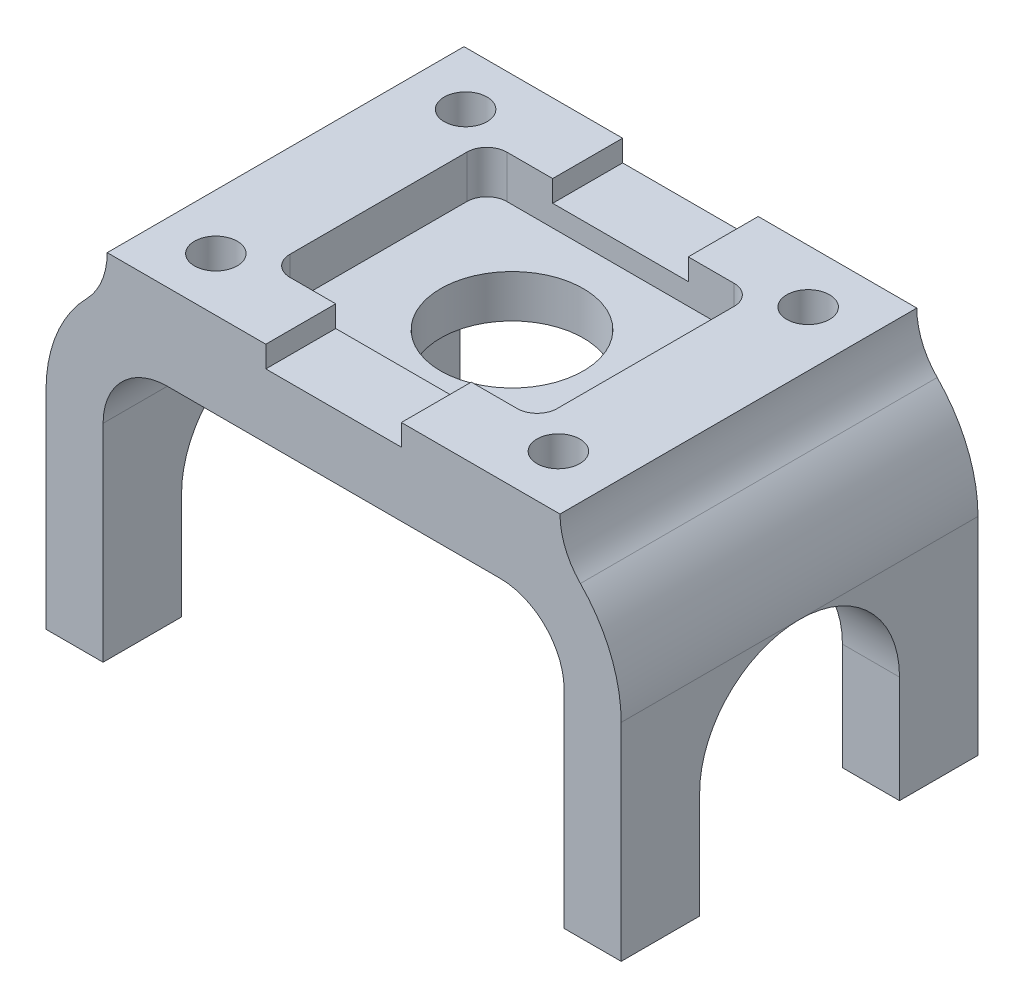
SolidWorks part; units mm, degrees
material "Plain Carbon Steel"
ref_plane "Front Plane" through (0, 0, 0) normal (0, 0, 1) x (1, 0, 0)
ref_plane "Top Plane" through (0, 0, 0) normal (0, 1, 0) x (1, 0, 0)
ref_plane "Right Plane" through (0, 0, 0) normal (1, 0, 0) x (0, 0, -1)
sketch "Sketch2" plane through (0, 0, 0) normal (0, 0, 1) x (1, 0, 0)
  line L0 (-29.591, 0) -> (29.591, 0)
  line L1 (41.021, -11.43) -> (41.021, -48.26)
  line L2 (41.021, -48.26) -> (51.181, -48.26)
  line L3 (51.181, -48.26) -> (51.181, -11.43)
  line L4 (40.2898, 15.24) -> (-40.2898, 15.24)
  line L5 (-51.181, -11.43) -> (-51.181, -48.26)
  line L6 (-51.181, -48.26) -> (-41.021, -48.26)
  line L7 (-41.021, -48.26) -> (-41.021, -11.43)
  line L8 (0, 0) -> (0, 94.6407) construction
  arc A0 (51.181, -11.43) -> (43.9202, 6.35) centre (25.781, -11.43) ccw
  arc A1 (43.9202, 6.35) -> (40.2898, 15.24) centre (52.9898, 15.24) cw
  arc A2 (-40.2898, 15.24) -> (-43.9202, 6.35) centre (-52.9898, 15.24) cw
  arc A3 (-43.9202, 6.35) -> (-51.181, -11.43) centre (-25.781, -11.43) ccw
  arc A4 (29.591, 0) -> (41.021, -11.43) centre (29.591, -11.43) cw
  arc A5 (-29.591, 0) -> (-41.021, -11.43) centre (-29.591, -11.43) ccw
  dimension "D1" = 36.83
  dimension "D4" = 12.7
  dimension "D5" = 25.4
  dimension "D2" = 10.16
  dimension "D3" = 15.24
  dimension "D6" = 82.042
  dimension "D7" = 63.5
extrude "Boss-Extrude1" add sketch "Sketch2" along normal mid plane 63.5
sketch "Sketch3" plane through (51.181, 0, 0) normal (1, 0, 0) x (0, 0, -1)
  line L0 (-17.78, -48.26) -> (17.78, -48.26)
  line L1 (-31.75, -48.26) -> (31.75, -48.26) construction
  line L2 (17.78, -48.26) -> (17.78, -29.21)
  line L3 (-17.78, -29.21) -> (-17.78, -48.26)
  line L4 (0, -48.26) -> (0, 0) construction
  arc A0 (17.78, -29.21) -> (-17.78, -29.21) centre (0, -29.21) ccw
  dimension "D1" = 19.05
  dimension "Cut_Width" = 35.56
extrude "Cut-Extrude1" cut sketch "Sketch3" against normal through all
sketch "Sketch4" plane through (0, 15.24, 0) normal (0, 1, 0) x (1, 0, 0)
  line L0 (40.2898, 31.75) -> (-40.2898, 31.75) construction
  line L1 (-20.2238, 19.304) -> (20.2238, 19.304)
  line L2 (-23.7798, 15.748) -> (-23.7798, -15.748)
  line L3 (-20.2238, -19.304) -> (20.2238, -19.304)
  line L4 (23.7798, 15.748) -> (23.7798, -15.748)
  line L5 (-23.7798, -19.304) -> (23.7798, 19.304) construction
  line L6 (-40.2898, -31.75) -> (-40.2898, 31.75) construction
  arc A0 (-23.7798, -15.748) -> (-20.2238, -19.304) centre (-20.2238, -15.748) ccw
  arc A1 (20.2238, -19.304) -> (23.7798, -15.748) centre (20.2238, -15.748) ccw
  arc A2 (20.2238, 19.304) -> (23.7798, 15.748) centre (20.2238, 15.748) cw
  arc A3 (-20.2238, 19.304) -> (-23.7798, 15.748) centre (-20.2238, 15.748) ccw
  dimension "D3" = 3.556
  dimension "D1" = 12.446
  dimension "D2" = 16.51
extrude "Cut-Extrude2" cut sketch "Sketch4" against normal blind 7.62
sketch "Sketch5" plane through (0, 0, 31.75) normal (0, 0, 1) x (1, 0, 0)
  line L0 (0, 0) -> (0, 29.0489) construction
  line L1 (-29.591, 0) -> (29.591, 0) construction
  line L2 (40.2898, 15.24) -> (-40.2898, 15.24) construction
  line L3 (12.065, 15.24) -> (-12.065, 15.24)
  line L4 (12.065, 15.24) -> (12.065, 11.43)
  line L5 (12.065, 11.43) -> (-12.065, 11.43)
  line L6 (-12.065, 15.24) -> (-12.065, 11.43)
  dimension "D1" = 24.13
  dimension "D2" = 3.81
extrude "Cut-Extrude3" cut sketch "Sketch5" against normal through all
sketch "Sketch6" plane through (0, 7.62, 0) normal (0, 1, 0) x (1, 0, 0)
  circle A0 centre (0, 0) radius 12.7
  dimension "Hole_Diameter" = 25.4
extrude "Cut-Extrude4" cut sketch "Sketch6" against normal up to next
sketch "Sketch7" plane through (0, 15.24, 0) normal (0, 1, 0) x (1, 0, 0)
  line L0 (-57.8306, 0) -> (65.0092, 0) construction
  line L1 (0, -38.3252) -> (0, 42.5913) construction
  circle A0 centre (-30.48, 22.225) radius 3.81
  circle A1 centre (30.48, 22.225) radius 3.81
  circle A2 centre (30.48, -22.225) radius 3.81
  circle A3 centre (-30.48, -22.225) radius 3.81
  dimension "D1" = 7.62
  dimension "D2" = 60.96
  dimension "D3" = 44.45
extrude "Cut-Extrude5" cut sketch "Sketch7" against normal up to next
sketch "Sketch8" [suppressed] plane through (0, 7.62, 0) normal (0, 1, 0) x (1, 0, 0)
  line L0 (12.065, 38.354) -> (-12.065, 38.354) construction
  line L1 (-11.0798, -25.654) -> (11.0798, -25.654)
  line L2 (-11.0798, -25.654) -> (-11.0798, 25.654)
  line L3 (-11.0798, 25.654) -> (11.0798, 25.654)
  line L4 (11.0798, -25.654) -> (11.0798, 25.654)
  line L5 (-11.0798, -25.654) -> (11.0798, 25.654) construction
  line L6 (-11.0798, 25.654) -> (11.0798, -25.654) construction
  line L7 (23.7798, -34.798) -> (23.7798, 34.798) construction
  point P0 (0, 0)
  dimension "D1" = 12.7
  dimension "D2" = 12.7
extrude "Cut-Extrude6" [suppressed] cut sketch "Sketch8" against normal through all
